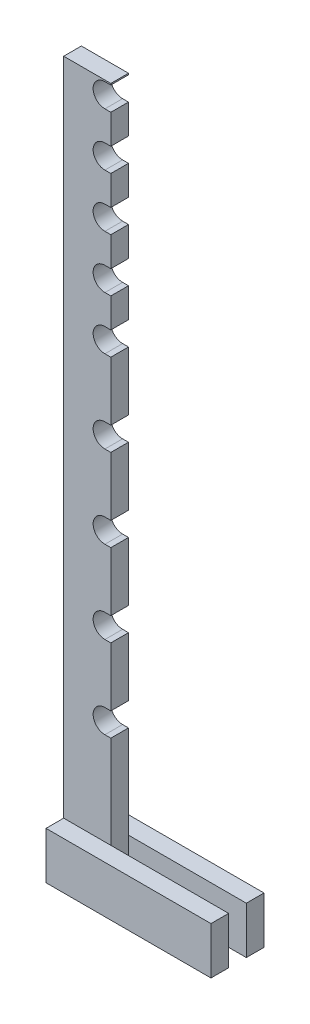
SolidWorks part; units mm, degrees
material "Maple"
ref_plane "Front" through (0, 0, 0) normal (0, 0, 1) x (1, 0, 0)
ref_plane "Top" through (0, 0, 0) normal (0, 1, 0) x (1, 0, 0)
ref_plane "Right" through (0, 0, 0) normal (1, 0, 0) x (0, 0, -1)
sketch "Sketch1" plane through (0, 0, 0) normal (0, 0, 1) x (1, 0, 0)
  line L10 (0, 0) -> (50.8, 0)
  line L14 (0, 0) -> (0, 762)
  line L15 (0, 762) -> (50.8, 762)
  line L16 (50.8, 0) -> (50.8, 762)
  dimension "D1" = 762
  dimension "D2" = 50.8
extrude "Boss-Extrude1" add sketch "Sketch1" along normal mid plane 19.05
sketch "Sketch3" plane through (0, 0, 9.525) normal (0, 0, 1) x (1, 0, 0)
  line L1 (0, 0) -> (177.8, 0)
  line L2 (0, 0) -> (0, 50.8)
  line L3 (0, 50.8) -> (177.8, 50.8)
  line L4 (177.8, 0) -> (177.8, 50.8)
  dimension "D1" = 50.8
  dimension "D2" = 177.8
extrude "Boss-Extrude2" add sketch "Sketch3" along normal blind 19.05 separate body
mirror "Mirror1" about plane through (0, 0, 0) normal (0, 0, 1) of bodies 182
sketch "Sketch2" plane through (0, 0, 9.525) normal (0, 0, 1) x (1, 0, 0)
  line L2 (44.45, 163.576) -> (50.8, 163.576) construction
  line L3 (50.8, 0) -> (50.8, 762) construction
  line L4 (44.45, 163.576) -> (44.45, 762) construction
  line L5 (50.8, 762) -> (0, 762) construction
  line L7 (44.45, 176.276) -> (50.8, 176.276)
  line L8 (44.45, 150.876) -> (50.8, 150.876)
  line L9 (50.8, 176.276) -> (50.8, 150.876)
  arc A0 (44.45, 176.276) -> (44.45, 150.876) centre (44.45, 163.576) ccw
  dimension "D1" = 25.4
  dimension "D2" = 163.576
  dimension "D3" = 6.35
extrude "Cut-Extrude1" cut sketch "Sketch2" against normal through all
pattern_linear "LPattern1" [suppressed] count 9 spacing 71.628
pattern_linear "LPattern4" [suppressed] count 6 spacing 50.8
sketch "Sketch4" [suppressed] plane through (0, 0, -9.525) normal (0, 0, -1) x (-1, 0, 0)
  line L0 (-44.45, 404.876) -> (-50.8, 404.876) construction
  line L1 (-44.45, 404.876) -> (-50.8, 404.876)
  line L2 (-50.8, 430.276) -> (-44.45, 430.276) construction
  line L3 (-50.8, 430.276) -> (-44.45, 430.276)
  line L4 (-50.8, 430.276) -> (-50.8, 404.876)
  line L5 (-50.8, 531.876) -> (-50.8, 506.476)
  line L6 (-44.45, 506.476) -> (-50.8, 506.476)
  line L7 (-50.8, 531.876) -> (-44.45, 531.876)
  line L8 (-50.8, 633.476) -> (-50.8, 608.076)
  line L9 (-44.45, 608.076) -> (-50.8, 608.076)
  line L10 (-50.8, 633.476) -> (-44.45, 633.476)
  line L11 (-50.8, 735.076) -> (-50.8, 709.676)
  line L12 (-44.45, 709.676) -> (-50.8, 709.676)
  line L13 (-50.8, 735.076) -> (-44.45, 735.076)
  arc A0 (-44.45, 404.876) -> (-44.45, 430.276) centre (-44.45, 417.576) ccw construction
  arc A1 (-44.45, 404.876) -> (-44.45, 430.276) centre (-44.45, 417.576) ccw
  arc A2 (-44.45, 506.476) -> (-44.45, 531.876) centre (-44.45, 519.176) ccw
  arc A3 (-44.45, 608.076) -> (-44.45, 633.476) centre (-44.45, 620.776) ccw
  arc A4 (-44.45, 709.676) -> (-44.45, 735.076) centre (-44.45, 722.376) ccw
  dimension "D2" = 101.6
  dimension "D1" = 4
extrude "Cut-Extrude2" [suppressed] cut sketch "Sketch4" against normal through all
pattern_linear "LPattern5" [suppressed] count 2 spacing 38.1
pattern_linear "LPattern6" count 5 spacing 88.9 along (0, 1, 0) of "Cut-Extrude1"
sketch "Sketch5" plane through (0, 0, -9.525) normal (0, 0, -1) x (-1, 0, 0)
  line L0 (-44.45, 531.876) -> (-50.8, 531.876) construction
  line L1 (-44.45, 531.876) -> (-50.8, 531.876)
  line L2 (-50.8, 506.476) -> (-44.45, 506.476) construction
  line L3 (-50.8, 506.476) -> (-44.45, 506.476)
  line L4 (-50.8, 531.876) -> (-50.8, 506.476)
  line L5 (-50.8, 589.026) -> (-50.8, 563.626)
  line L6 (-50.8, 563.626) -> (-44.45, 563.626)
  line L7 (-44.45, 589.026) -> (-50.8, 589.026)
  line L8 (-50.8, 646.176) -> (-50.8, 620.776)
  line L9 (-50.8, 620.776) -> (-44.45, 620.776)
  line L10 (-44.45, 646.176) -> (-50.8, 646.176)
  line L11 (-50.8, 703.326) -> (-50.8, 677.926)
  line L12 (-50.8, 677.926) -> (-44.45, 677.926)
  line L13 (-44.45, 703.326) -> (-50.8, 703.326)
  line L14 (-50.8, 760.476) -> (-50.8, 735.076)
  line L15 (-50.8, 735.076) -> (-44.45, 735.076)
  line L16 (-44.45, 760.476) -> (-50.8, 760.476)
  arc A0 (-44.45, 506.476) -> (-44.45, 531.876) centre (-44.45, 519.176) ccw construction
  arc A1 (-44.45, 506.476) -> (-44.45, 531.876) centre (-44.45, 519.176) ccw
  arc A2 (-44.45, 563.626) -> (-44.45, 589.026) centre (-44.45, 576.326) ccw
  arc A3 (-44.45, 620.776) -> (-44.45, 646.176) centre (-44.45, 633.476) ccw
  arc A4 (-44.45, 677.926) -> (-44.45, 703.326) centre (-44.45, 690.626) ccw
  arc A5 (-44.45, 735.076) -> (-44.45, 760.476) centre (-44.45, 747.776) ccw
  dimension "D2" = 57.15
  dimension "D1" = 5
extrude "Cut-Extrude3" cut sketch "Sketch5" against normal through all
